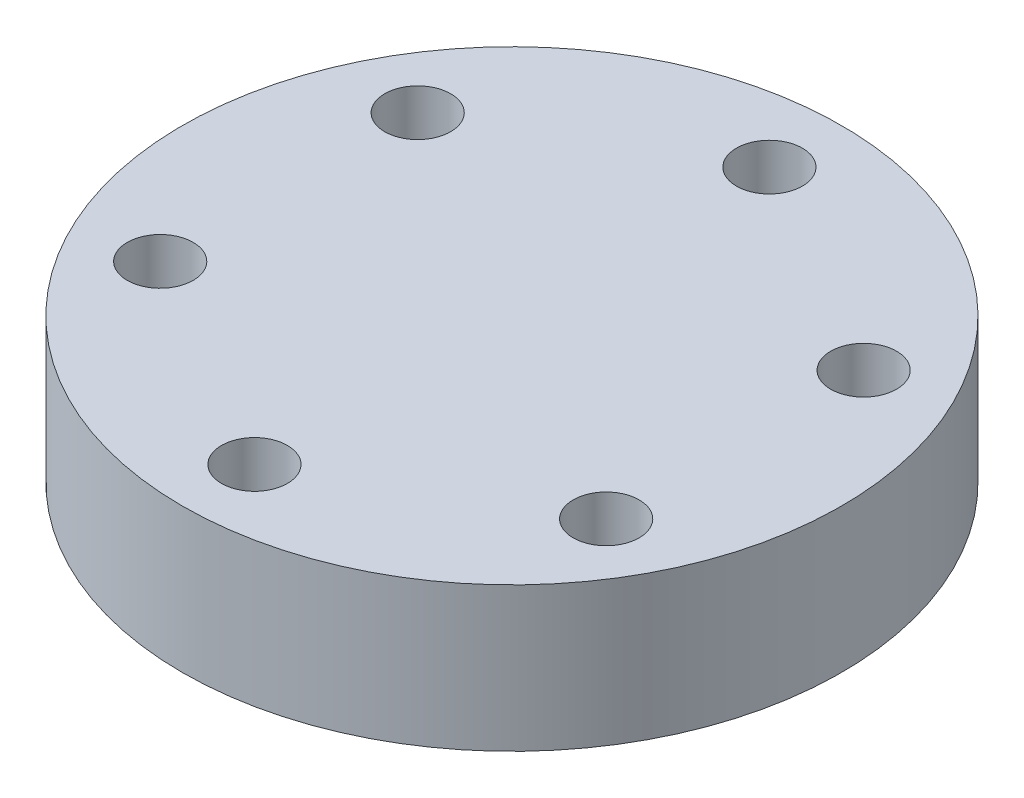
SolidWorks part; units mm, degrees
material "ABS"
ref_plane "前视基准面" through (0, 0, 0) normal (0, 0, 1) x (1, 0, 0)
ref_plane "上视基准面" through (0, 0, 0) normal (0, 1, 0) x (1, 0, 0)
ref_plane "右视基准面" through (0, 0, 0) normal (1, 0, 0) x (0, 0, -1)
other "Configuration Table"
sketch "草图1" plane through (0, 0, 0) normal (0, 1, 0) x (1, 0, 0)
  circle A0 centre (0, 0) radius 16
  dimension "D1" = 32
extrude "凸台-拉伸1" add sketch "草图1" along normal blind 5
sketch "草图2" plane through (0, 5, 0) normal (0, 1, 0) x (1, 0, 0)
  circle A0 centre (0, 0) radius 16
  circle A1 centre (0, 0) radius 16 construction
extrude "凸台-拉伸2" add sketch "草图2" along normal blind 2
sketch "草图3" plane through (0, 7, 0) normal (0, 1, 0) x (1, 0, 0)
  circle A0 centre (0, 0) radius 12.5 construction
  circle A1 centre (0, 12.5) radius 1.6
  circle A2 centre (10.8253, 6.25) radius 1.6
  circle A3 centre (10.8253, -6.25) radius 1.6
  circle A4 centre (0, -12.5) radius 1.6
  circle A5 centre (-10.8253, -6.25) radius 1.6
  circle A6 centre (-10.8253, 6.25) radius 1.6
  dimension "D1" = 25
  dimension "D2" = 3.2
extrude "切除-拉伸1" cut sketch "草图3" against normal through all
